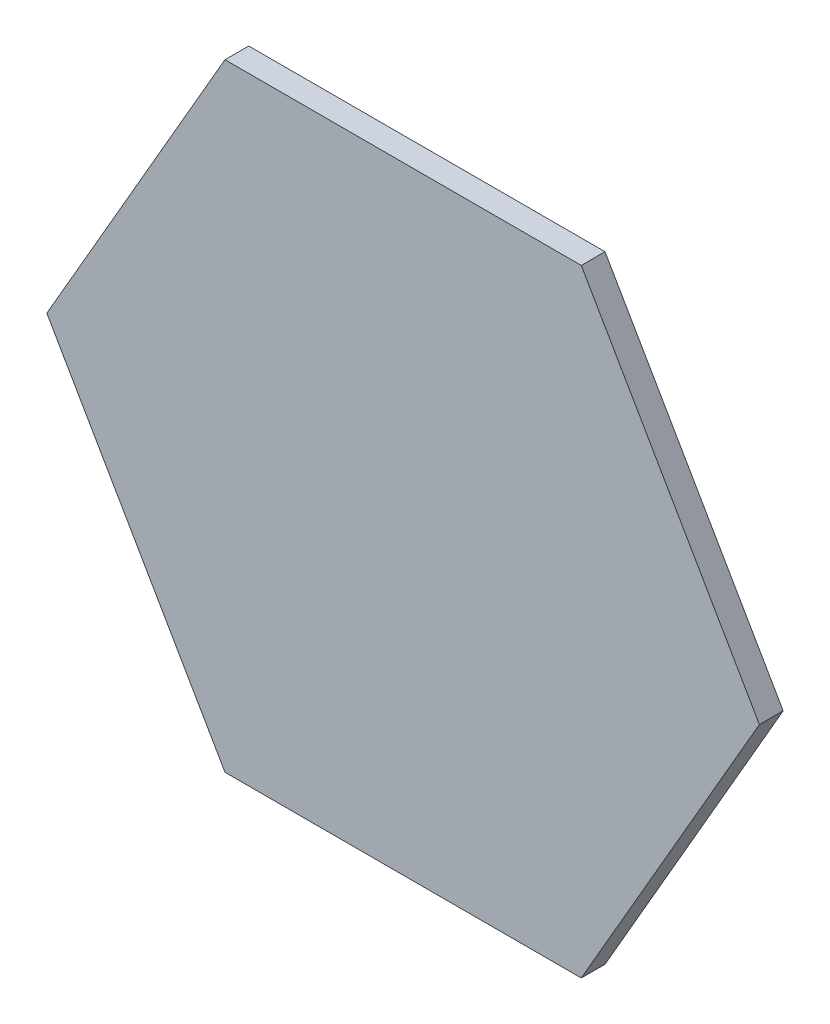
SolidWorks part; units mm, degrees
ref_plane "Front Plane" through (0, 0, 0) normal (0, 0, 1) x (1, 0, 0)
ref_plane "Top Plane" through (0, 0, 0) normal (0, 1, 0) x (1, 0, 0)
ref_plane "Right Plane" through (0, 0, 0) normal (1, 0, 0) x (0, 0, -1)
sketch "Sketch1" plane through (0, 0, 0) normal (0, 0, 1) x (1, 0, 0)
  line L1 (75, 129.9038) -> (-75, 129.9038)
  line L2 (-75, 129.9038) -> (-150, 0)
  line L3 (-150, 0) -> (-75, -129.9038)
  line L4 (-75, -129.9038) -> (75, -129.9038)
  line L5 (75, -129.9038) -> (150, 0)
  line L6 (150, 0) -> (75, 129.9038)
  circle A0 centre (0, 0) radius 129.9038 construction
  dimension "D1" = 150
extrude "Boss-Extrude1" add sketch "Sketch1" along normal blind 10
